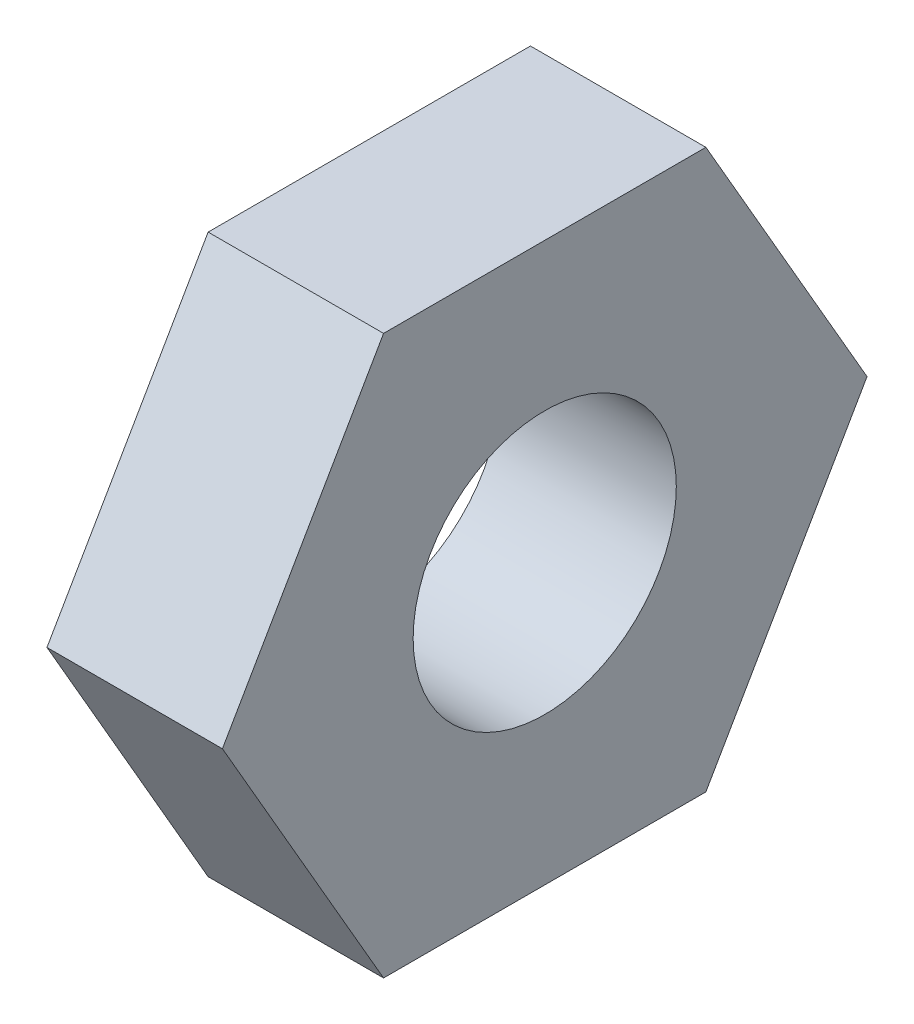
SolidWorks part; units mm, degrees
material "Alloy Steel"
ref_plane "Front Plane" through (0, 0, 0) normal (0, 0, 1) x (1, 0, 0)
ref_plane "Top Plane" through (0, 0, 0) normal (0, 1, 0) x (1, 0, 0)
ref_plane "Right Plane" through (0, 0, 0) normal (1, 0, 0) x (0, 0, -1)
other "PropertyManager"
sketch "BaseNutSketch" plane through (0, 0, 0) normal (1, 0, 0) x (0, 0, -1)
  line L1 (2.0207, 3.5) -> (-2.0207, 3.5)
  line L2 (-2.0207, 3.5) -> (-4.0415, 0)
  line L3 (-4.0415, 0) -> (-2.0207, -3.5)
  line L4 (-2.0207, -3.5) -> (2.0207, -3.5)
  line L5 (2.0207, -3.5) -> (4.0415, 0)
  line L6 (4.0415, 0) -> (2.0207, 3.5)
  circle A0 centre (0, 0) radius 3.5 construction
  circle A1 centre (0, 0) radius 1.65
  dimension "Width_flats" = 7
  dimension "Tap_drill" = 3.3
extrude "BaseNut" add sketch "BaseNutSketch" along normal blind 2.2
cosmetic thread "Thread"
other "Freeze***"
